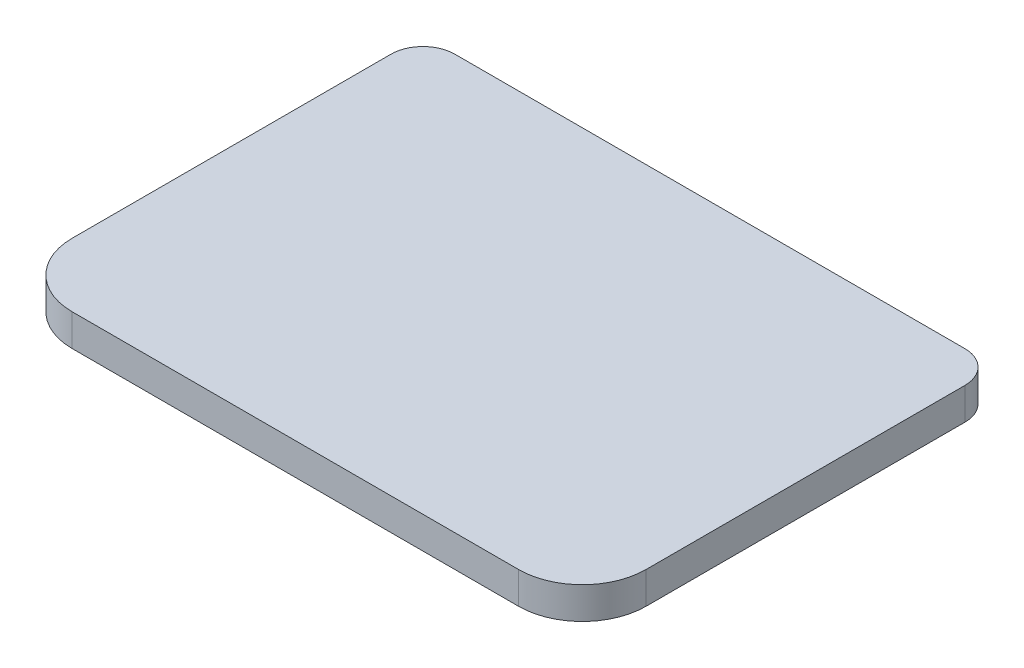
SolidWorks part; units mm, degrees
ref_plane "Front Plane" through (0, 0, 0) normal (0, 0, 1) x (1, 0, 0)
ref_plane "Top Plane" through (0, 0, 0) normal (0, 1, 0) x (1, 0, 0)
ref_plane "Right Plane" through (0, 0, 0) normal (1, 0, 0) x (0, 0, -1)
sketch "Sketch1" plane through (0, 0, 0) normal (0, 1, 0) x (1, 0, 0)
  line L1 (-28.575, 20.6375) -> (28.575, 20.6375)
  line L2 (-28.575, 20.6375) -> (-28.575, -20.6375)
  line L3 (-28.575, -20.6375) -> (28.575, -20.6375)
  line L4 (28.575, 20.6375) -> (28.575, -20.6375)
  line L5 (-28.575, 20.6375) -> (28.575, -20.6375) construction
  line L6 (-28.575, -20.6375) -> (28.575, 20.6375) construction
  point P0 (0, 0)
  dimension "D1" = 57.15
  dimension "D2" = 41.275
extrude "Boss-Extrude1" add sketch "Sketch1" along normal blind 3.175
sketch "Sketch2" plane through (0, 3.175, 0) normal (0, 1, 0) x (1, 0, 0)
  line L2 (-28.575, -20.6375) -> (28.575, -20.6375) construction
  line L3 (-28.575, -20.6375) -> (28.575, -20.6375)
  line L5 (28.575, -20.6375) -> (28.575, 20.6375) construction
  arc A0 (-23.4462, -17.2183) -> (23.4462, -17.2183) centre (0, -26.9875) cw
  arc A1 (-28.575, -20.6375) -> (-23.4462, -17.2183) centre (-28.575, -15.0813) ccw
  arc A2 (23.4462, -17.2183) -> (28.575, -20.6375) centre (28.575, -15.0812) ccw
  dimension "D1" = 25.4
  dimension "D2" = 6.35
fillet "Fillet1" radius 6.35 2 edges at (28.575, 1.5875, 20.6375) (-28.575, 1.5875, 20.6375)
fillet "Fillet2" radius 3.175 2 edges at (28.575, 1.5875, -20.6375) (-28.575, 1.5875, -20.6375)
